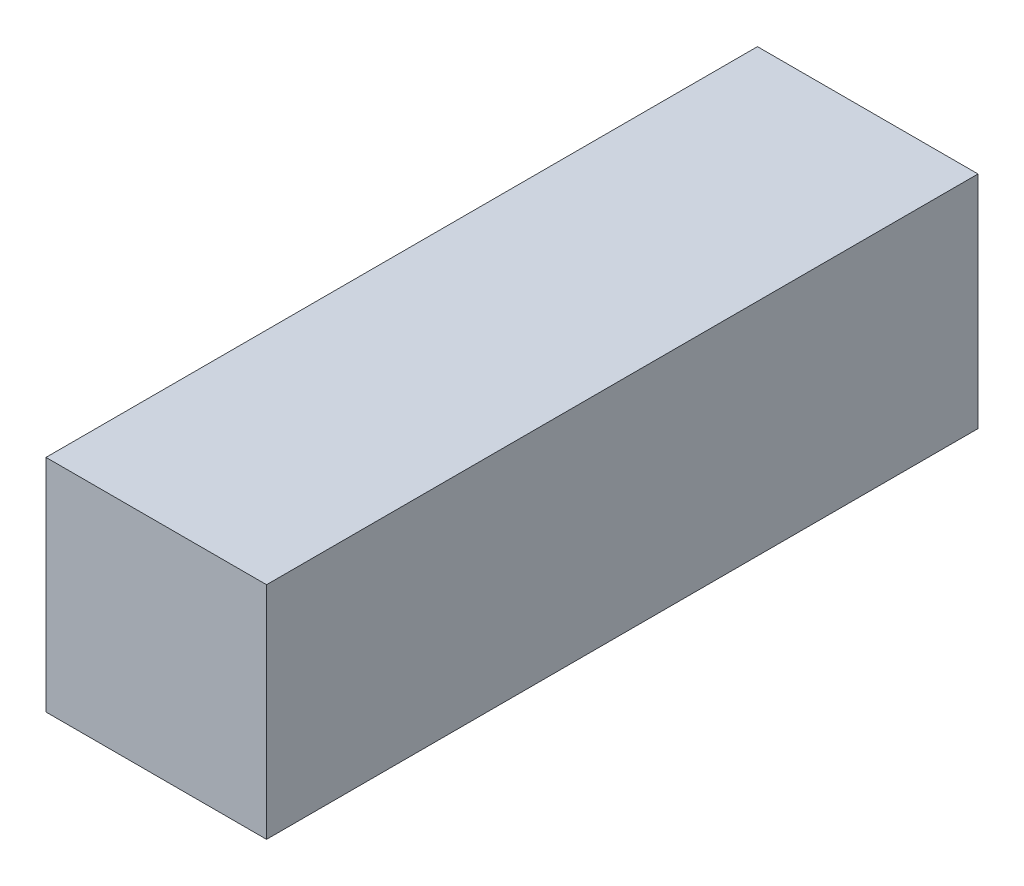
SolidWorks part; units mm, degrees
ref_plane "Front Plane" through (0, 0, 0) normal (0, 0, 1) x (1, 0, 0)
ref_plane "Top Plane" through (0, 0, 0) normal (0, 1, 0) x (1, 0, 0)
ref_plane "Right Plane" through (0, 0, 0) normal (1, 0, 0) x (0, 0, -1)
sketch "Sketch1" plane through (0, 0, 0) normal (0, 0, 1) x (1, 0, 0)
  line L1 (-3.1, 3.1) -> (3.1, 3.1)
  line L2 (-3.1, 3.1) -> (-3.1, -3.1)
  line L3 (-3.1, -3.1) -> (3.1, -3.1)
  line L4 (3.1, 3.1) -> (3.1, -3.1)
  line L5 (-3.1, 3.1) -> (3.1, -3.1) construction
  line L6 (-3.1, -3.1) -> (3.1, 3.1) construction
  point P0 (0, 0)
  dimension "D1" = 6.2
  dimension "D2" = 6.2
extrude "Boss-Extrude1" add sketch "Sketch1" along normal blind 20
